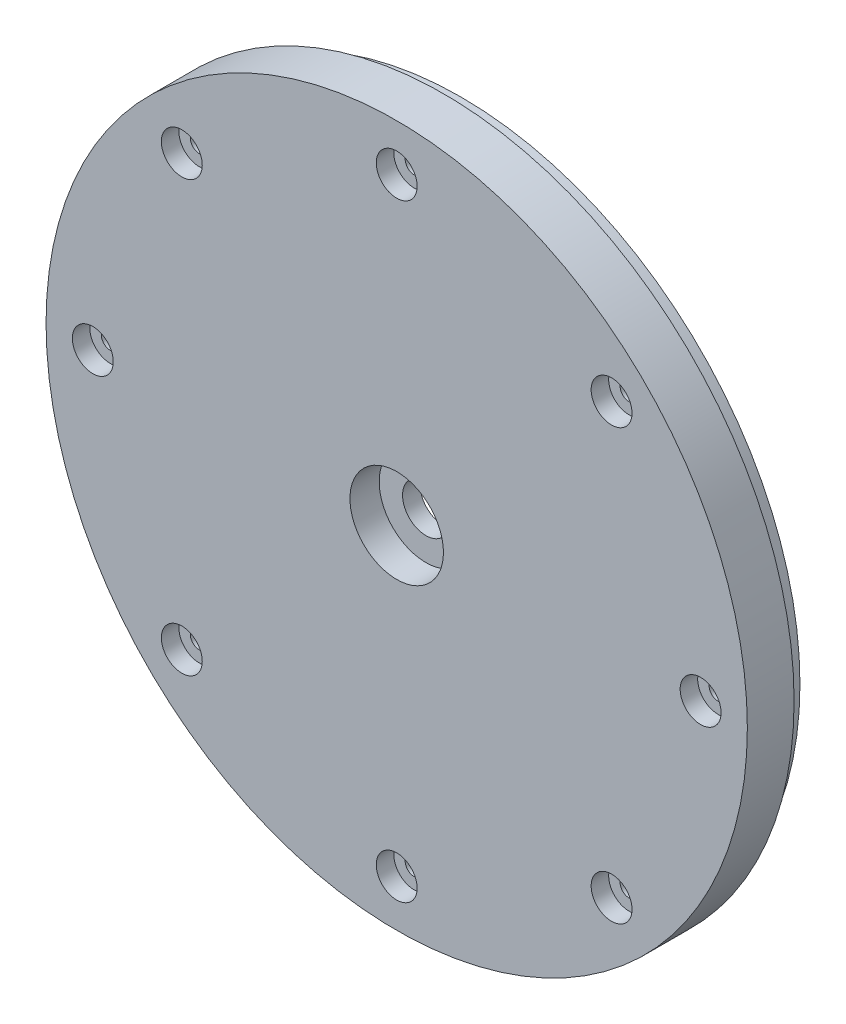
SolidWorks part; units mm, degrees
ref_plane "Front Plane" through (0, 0, 0) normal (0, 0, 1) x (1, 0, 0)
ref_plane "Top Plane" through (0, 0, 0) normal (0, 1, 0) x (1, 0, 0)
ref_plane "Right Plane" through (0, 0, 0) normal (1, 0, 0) x (0, 0, -1)
sketch "Sketch1" plane through (0, 0, 0) normal (0, 0, 1) x (1, 0, 0)
  line L0 (0, 0) -> (-36.7696, 36.7696) construction
  circle A1 centre (0, 0) radius 60
  circle A2 centre (0, 0) radius 4
  circle A3 centre (-36.7696, 36.7696) radius 1.55
  circle A4 centre (0, 52) radius 1.55
  circle A5 centre (36.7696, 36.7696) radius 1.55
  circle A6 centre (52, 0) radius 1.55
  circle A7 centre (36.7696, -36.7696) radius 1.55
  circle A8 centre (0, -52) radius 1.55
  circle A9 centre (-36.7696, -36.7696) radius 1.55
  circle A10 centre (-52, 0) radius 1.55
  point P22 (0, 0)
  dimension "D1" = 8
extrude "Boss-Extrude2" add sketch "Sketch1" along normal blind 8
sketch "Sketch2" plane through (0, 0, 8) normal (0, 0, 1) x (1, 0, 0)
  circle A0 centre (0, 0) radius 8
extrude "Cut-Extrude1" cut sketch "Sketch2" against normal blind 5
sketch "Sketch3" plane through (0, 0, 8) normal (0, 0, 1) x (1, 0, 0)
  circle A0 centre (0, 52) radius 3.5
  circle A1 centre (36.7696, 36.7696) radius 3.5
  circle A2 centre (52, 0) radius 3.5
  circle A3 centre (36.7696, -36.7696) radius 3.5
  circle A4 centre (0, -52) radius 3.5
  circle A5 centre (-36.7696, -36.7696) radius 3.5
  circle A6 centre (-52, 0) radius 3.5
  circle A7 centre (-36.7696, 36.7696) radius 3.5
  point P19 (0, 0)
  dimension "D1" = 8
extrude "Cut-Extrude2" cut sketch "Sketch3" against normal blind 3
sketch "Sketch4" plane through (0, 0, 0) normal (0, 0, -1) x (-1, 0, 0)
  circle A0 centre (0, 0) radius 58
  circle A1 centre (0, 0) radius 56
extrude "Boss-Extrude3" add sketch "Sketch4" along normal blind 3
